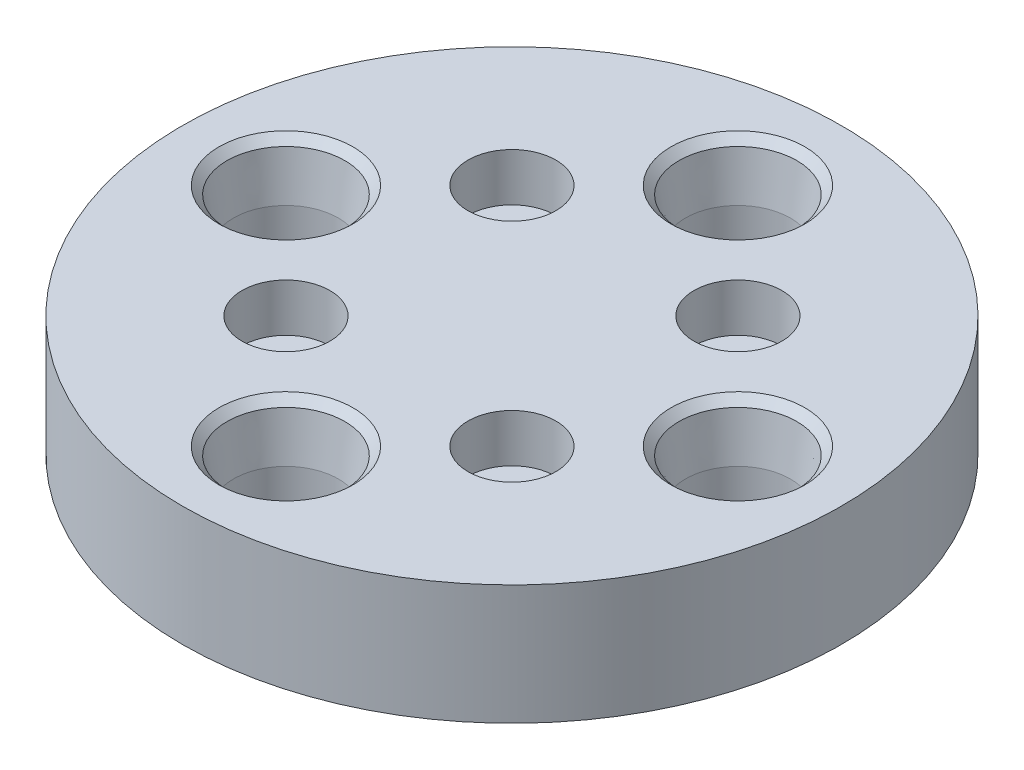
SolidWorks part; units mm, degrees
ref_plane "Front Plane" through (0, 0, 0) normal (0, 0, 1) x (1, 0, 0)
ref_plane "Top Plane" through (0, 0, 0) normal (0, 1, 0) x (1, 0, 0)
ref_plane "Right Plane" through (0, 0, 0) normal (1, 0, 0) x (0, 0, -1)
sketch "Sketch1" plane through (0, 0, 0) normal (0, 1, 0) x (1, 0, 0)
  circle A0 centre (0, 0) radius 16.5
  dimension "D1" = 33
extrude "Boss-Extrude1" add sketch "Sketch1" against normal blind 6
sketch "Sketch25" plane through (0, -6, 0) normal (0, -1, 0) x (1, 0, 0)
  circle A0 centre (0, 0) radius 10.25
  dimension "D1" = 20.5
extrude "Boss-Extrude2" add sketch "Sketch25" along normal blind 2
sketch "Sketch2" plane through (0, 0, 0) normal (0, 1, 0) x (1, 0, 0)
  line L1 (-8, -8) -> (8, -8) construction
  line L2 (-8, -8) -> (-8, 8) construction
  line L3 (-8, 8) -> (8, 8) construction
  line L4 (8, -8) -> (8, 8) construction
  line L5 (-8, -8) -> (8, 8) construction
  line L6 (-8, 8) -> (8, -8) construction
  circle A0 centre (0, 0) radius 11.3137 construction
  point P3 (0, 11.3137)
  dimension "D1" = 16
sketch "Sketch23" plane through (0, 0, 0) normal (0, 1, 0) x (1, 0, 0)
  line L0 (0, 0) -> (5.6569, 5.6569) construction
  line L1 (0, 0) -> (0, 25.8205) construction
  circle A0 centre (0, 0) radius 8 construction
  point P1 (5.6569, 5.6569)
  point P8 (5.6569, 5.6569)
  dimension "D2" = 16
  dimension "D1" = 45
sketch "Sketch22" plane through (1.4462, 0, 24.411) normal (0, 1, 0) x (1, 0, 0)
  line L0 (-1.4462, 35.7247) -> (6.6512, 35.7247) construction
  circle A0 centre (-1.4462, 35.7247) radius 2.25
  dimension "D1" = 4.5
extrude "Cut-Extrude1" cut sketch "Sketch22" against normal through all
ref_plane "Plane1" through (0, 0, -11.3137) normal (1, 0, 0) x (0, 0, -1)
sketch "Sketch3" plane through (0, 0, -23.4507) normal (1, 0, 0) x (0, 0, -1)
  line L0 (-12.137, 0) -> (-8.7852, 0)
  line L1 (-8.7852, 0) -> (-9.1852, -0.4)
  line L2 (-9.1852, -0.4) -> (-9.512, -2.725)
  line L3 (-9.512, -2.725) -> (-9.512, -5.45)
  line L4 (-9.512, -5.45) -> (-9.887, -5.825)
  line L5 (-9.887, -5.825) -> (-12.137, -5.825)
  line L6 (-12.137, -5.825) -> (-12.137, 0)
  dimension "D1" = 2.25
  dimension "D2" = 2.625
  dimension "D3" = 45
  dimension "D4" = 5.45
  dimension "D5" = 8
  dimension "D6" = 0.4
  dimension "D7" = 2.725
revolve "Cut-Revolve1" cut sketch "Sketch3" angle 360 about L6
other "heatset insert metric<1>"
hole_wizard "CBORE for M2 Hex Socket Head Cap Screw1" positions "Sketch23" profile "Sketch24" counterbore size "M2" standard "DIN" end condition through all
sketch "Sketch24" plane through (5.6569, 0, -5.6569) normal (1, 0, 0) x (0, 0, 1)
  line L0 (0, 0) -> (0, 8)
  line L1 (0, 8) -> (1.2, 8)
  line L3 (1.2, 8) -> (1.2, 2.4)
  line L4 (1.2, 2.4) -> (2.2, 2.4)
  line L5 (2.2, 2.4) -> (2.2, 0)
  line L7 (2.2, 0) -> (0, 0)
  line L11 (0, -6.35) -> (0, 107.95) construction
  dimension "Thru Hole Dia." = 2.4
  dimension "Thru Hole Depth" = 8
  dimension "C'Bore Dia." = 4.4
  dimension "C'Bore Depth" = 2.4
pattern_circular "CirPattern1" count 4 over 360 about axis through (0, 0, 0) along (0, 1, 0) of "CBORE for M2 Hex Socket Head Cap Screw1", "Cut-Extrude1", "Cut-Revolve1"
sketch "Sketch26" plane through (0, -8, 0) normal (0, -1, 0) x (1, 0, 0)
  circle A0 centre (0, 0) radius 4.5
  dimension "D1" = 9
extrude "Cut-Extrude2" cut sketch "Sketch26" against normal blind 4.5
equation "\"D1@Sketch22\"=\"nominal_size\" +0.5mm"
equation "\"D1@Sketch3\"=(\"nominal_size\"+.5mm)/2"
equation "\"D2@Sketch3\"=\"hole_diameter\"/2"
equation "\"D4@Sketch3\"=\"insert_length\"+0.75mm"
equation "\"D7@Sketch3\"=\"D4@Sketch3\"/2"
